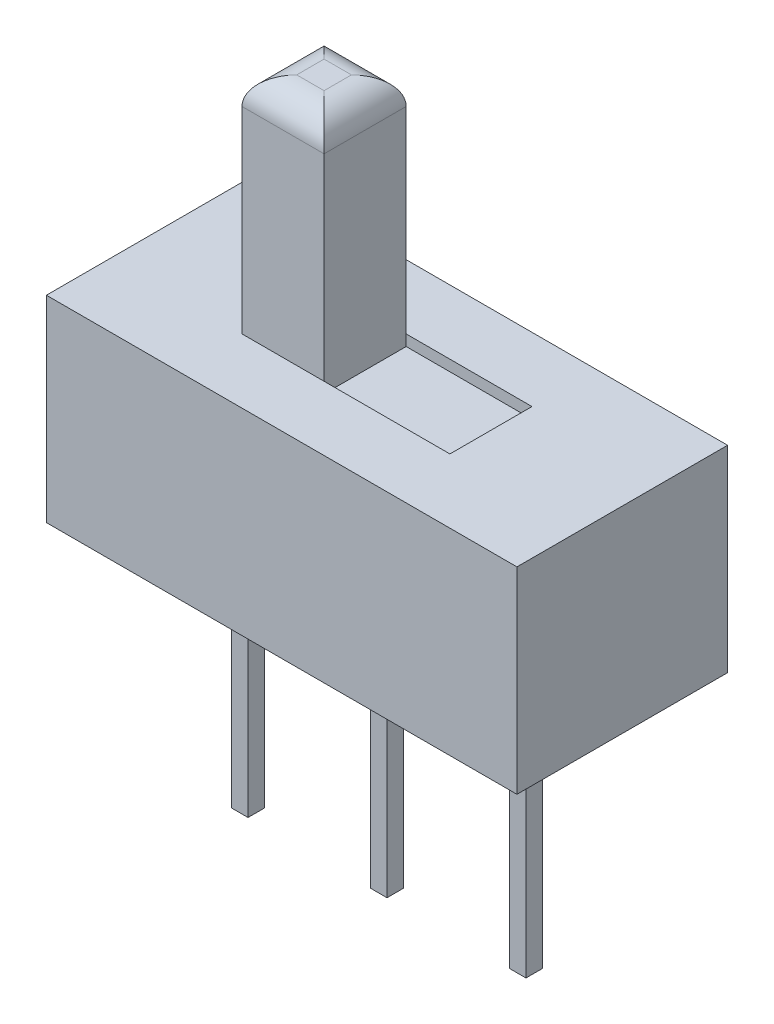
SolidWorks part; units mm, degrees
ref_plane "Front Plane" through (0, 0, 0) normal (0, 0, 1) x (1, 0, 0)
ref_plane "Top Plane" through (0, 0, 0) normal (0, 1, 0) x (1, 0, 0)
ref_plane "Right Plane" through (0, 0, 0) normal (1, 0, 0) x (0, 0, -1)
sketch "Sketch2" plane through (0, 0, 0) normal (0, 1, 0) x (1, 0, 0)
  line L1 (-4.3, -1.925) -> (4.3, -1.925)
  line L2 (-4.3, -1.925) -> (-4.3, 1.925)
  line L3 (-4.3, 1.925) -> (4.3, 1.925)
  line L4 (4.3, -1.925) -> (4.3, 1.925)
  line L5 (-4.3, -1.925) -> (4.3, 1.925) construction
  line L6 (-4.3, 1.925) -> (4.3, -1.925) construction
  point P0 (0, 0)
  dimension "D1" = 8.6
  dimension "D2" = 3.85
extrude "Boss-Extrude1" add sketch "Sketch2" along normal blind 3.6
sketch "Sketch3" plane through (0, 3.6, 0) normal (0, 1, 0) x (1, 0, 0)
  line L0 (-4.3, 1.925) -> (-4.3, -1.925) construction
  line L1 (-1.9, -0.75) -> (-0.4, -0.75)
  line L2 (-1.9, -0.75) -> (-1.9, 0.75)
  line L3 (-1.9, 0.75) -> (-0.4, 0.75)
  line L4 (-0.4, -0.75) -> (-0.4, 0.75)
  line L5 (-1.9, -0.75) -> (-0.4, 0.75) construction
  line L6 (-1.9, 0.75) -> (-0.4, -0.75) construction
  point P0 (-1.15, 0)
  dimension "D1" = 1.5
  dimension "D2" = 1.5
  dimension "D3" = 2.4
extrude "Boss-Extrude2" add sketch "Sketch3" along normal blind 4.1
sketch "Sketch4" plane through (0, 3.6, 0) normal (0, 1, 0) x (1, 0, 0)
  line L0 (4.3, -1.925) -> (4.3, 1.925) construction
  line L1 (-0.4, -0.75) -> (1.9, -0.75)
  line L2 (-0.4, -0.75) -> (-0.4, 0.75)
  line L3 (-0.4, 0.75) -> (1.9, 0.75)
  line L4 (1.9, -0.75) -> (1.9, 0.75)
  line L5 (-0.4, -0.75) -> (1.9, 0.75) construction
  line L6 (-0.4, 0.75) -> (1.9, -0.75) construction
  line L7 (-0.4, -0.75) -> (-0.4, 0.75) construction
  point P0 (0.75, 0)
  dimension "D1" = 1.5
  dimension "D2" = 2.4
extrude "Cut-Extrude1" cut sketch "Sketch4" against normal blind 0.2
fillet "Fillet1" radius 0.5 4 edges at (-1.15, 7.7, 0.75) (-1.9, 7.7, 0) (-1.15, 7.7, -0.75) (-0.4, 7.7, 0)
sketch "Sketch5" plane through (0, 0, 0) normal (0, -1, 0) x (1, 0, 0)
  line L0 (-1000, 0) -> (49000, 0) construction
  line L2 (-0.15, -0.15) -> (0.15, -0.15)
  line L3 (-0.15, -0.15) -> (-0.15, 0.15)
  line L4 (-0.15, 0.15) -> (0.15, 0.15)
  line L5 (0.15, -0.15) -> (0.15, 0.15)
  line L6 (-0.15, -0.15) -> (0.15, 0.15) construction
  line L7 (-0.15, 0.15) -> (0.15, -0.15) construction
  line L8 (-2.69, -0.15) -> (-2.39, -0.15)
  line L9 (-2.69, -0.15) -> (-2.69, 0.15)
  line L10 (-2.69, 0.15) -> (-2.39, 0.15)
  line L11 (-2.39, -0.15) -> (-2.39, 0.15)
  line L12 (-2.69, -0.15) -> (-2.39, 0.15) construction
  line L13 (-2.69, 0.15) -> (-2.39, -0.15) construction
  line L14 (2.39, -0.15) -> (2.69, -0.15)
  line L15 (2.39, -0.15) -> (2.39, 0.15)
  line L16 (2.39, 0.15) -> (2.69, 0.15)
  line L17 (2.69, -0.15) -> (2.69, 0.15)
  line L18 (2.39, -0.15) -> (2.69, 0.15) construction
  line L19 (2.39, 0.15) -> (2.69, -0.15) construction
  point P1 (0, 0)
  point P8 (-2.54, 0)
  point P13 (2.54, 0)
  dimension "D1" = 0.3
  dimension "D2" = 0.3
  dimension "D3" = 0.3
  dimension "D4" = 0.3
  dimension "D7" = 2.54
  dimension "D8" = 2.54
extrude "Boss-Extrude3" add sketch "Sketch5" along normal blind 4.6
sketch "Sketch7" plane through (0, -4.6, 0) normal (0, -1, 0) x (1, 0, 0)
  line L0 (0.15, 0.15) -> (-0.15, 0.15) construction
  circle A0 centre (0, 0) radius 0.15
  point P3 (0, 0.15)
  point P4 (0, 0)
